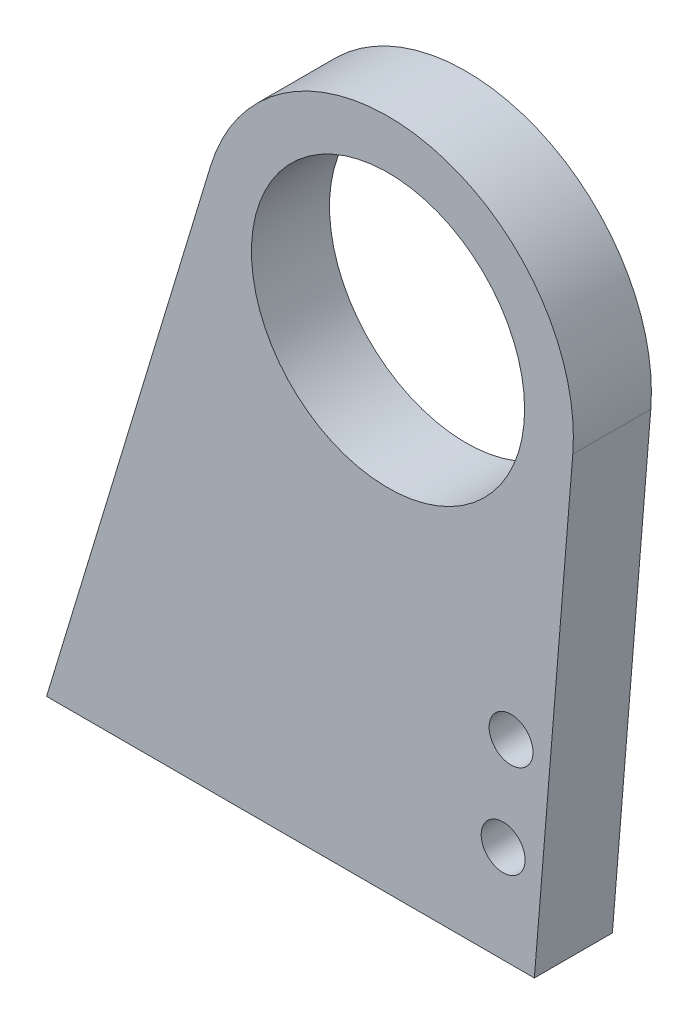
SolidWorks part; units mm, degrees
material "5052-O"
ref_plane "정면" through (0, 0, 0) normal (0, 0, 1) x (1, 0, 0)
ref_plane "윗면" through (0, 0, 0) normal (0, 1, 0) x (1, 0, 0)
ref_plane "우측면" through (0, 0, 0) normal (1, 0, 0) x (0, 0, -1)
sketch "스케치1" plane through (0, 0, 0) normal (0, 0, 1) x (1, 0, 0)
  line L0 (0, 0) -> (50, 0)
  line L1 (50, 0) -> (53.9376, 48.4613)
  line L2 (0, 0) -> (16.8161, 55.5087)
  circle A0 centre (35, 50) radius 19
  circle A1 centre (35, 50) radius 14
  dimension "D1" = 38
  dimension "D4" = 5
  dimension "D2" = 50
  dimension "D3" = 50
  dimension "D5" = 15
extrude "보스-돌출1" add sketch "스케치1" along normal blind 8 contours A0 L2 L0 L1 | A0 A1
hole_wizard "M4 여유 구멍1" positions "스케치2" profile "스케치3" hole size "M4" standard "ISO" end condition up to next
sketch "스케치2" plane through (0, 0, 8) normal (0, 0, 1) x (1, 0, 0)
  line L0 (47.6092, 19.9672) -> (46.7993, 10)
  line L2 (50, 0) -> (53.9376, 48.4613) construction
  line L3 (0, 0) -> (50, 0) construction
  point P0 (46.7993, 10)
  point P2 (47.6092, 19.9672)
  dimension "D1" = 10
  dimension "D2" = 4
  dimension "D3" = 10
sketch "스케치3" plane through (46.7993, 10, 8) normal (1, 0, 0) x (0, -1, 0)
  line L0 (0, 0) -> (0, 8)
  line L1 (0, 8) -> (2.25, 8)
  line L2 (2.25, 8) -> (2.25, 0)
  line L5 (2.25, 0) -> (0, 0)
  line L11 (0, -6.35) -> (0, 107.95) construction
  dimension "관통 구멍 지름" = 4.5
  dimension "관통 구멍 깊이" = 8
hole_wizard "M3 나사 구멍1" positions "스케치4" profile "스케치5" tap size "M3" standard "ISO"
sketch "스케치4" plane through (0, 0, 0) normal (0, -1, 0) x (-1, 0, 0)
  line L0 (-10, -4) -> (-40, -4)
  line L2 (0, 0) -> (-50, 0) construction
  line L3 (-50, -8) -> (-50, 0) construction
  point P0 (-10, -4)
  point P2 (-40, -4)
  point P8 (-25, -4)
  point P11 (-25, 0)
  point P14 (-50, -4)
  dimension "D1" = 30
sketch "스케치5" plane through (10, 0, 4) normal (1, 0, 0) x (0, 0, -1)
  line L0 (0, 0) -> (0, 9.2511)
  line L1 (0, 9.2511) -> (1.25, 8.5)
  line L2 (1.25, 8.5) -> (1.25, 0.275)
  line L3 (1.25, 0.275) -> (1.525, 0)
  line L5 (1.525, 0) -> (0, 0)
  line L6 (-1.25, 0.275) -> (-1.525, 0) construction
  line L10 (0, 9.2511) -> (-1.25, 8.5) construction
  line L11 (0, -6.35) -> (0, 107.95) construction
  dimension "탭 드릴 지름" = 2.5
  dimension "탭 드릴 깊이" = 8.5
  dimension "표면 카운터싱크 지름" = 3.05
  dimension "표면 카운터싱크 각도" = 90
  dimension "드릴 각도" = 118
cosmetic thread "구멍 나사산1" parameters "D1"=6, "D2"=3
cosmetic thread "구멍 나사산2" parameters "D1"=6, "D2"=3
